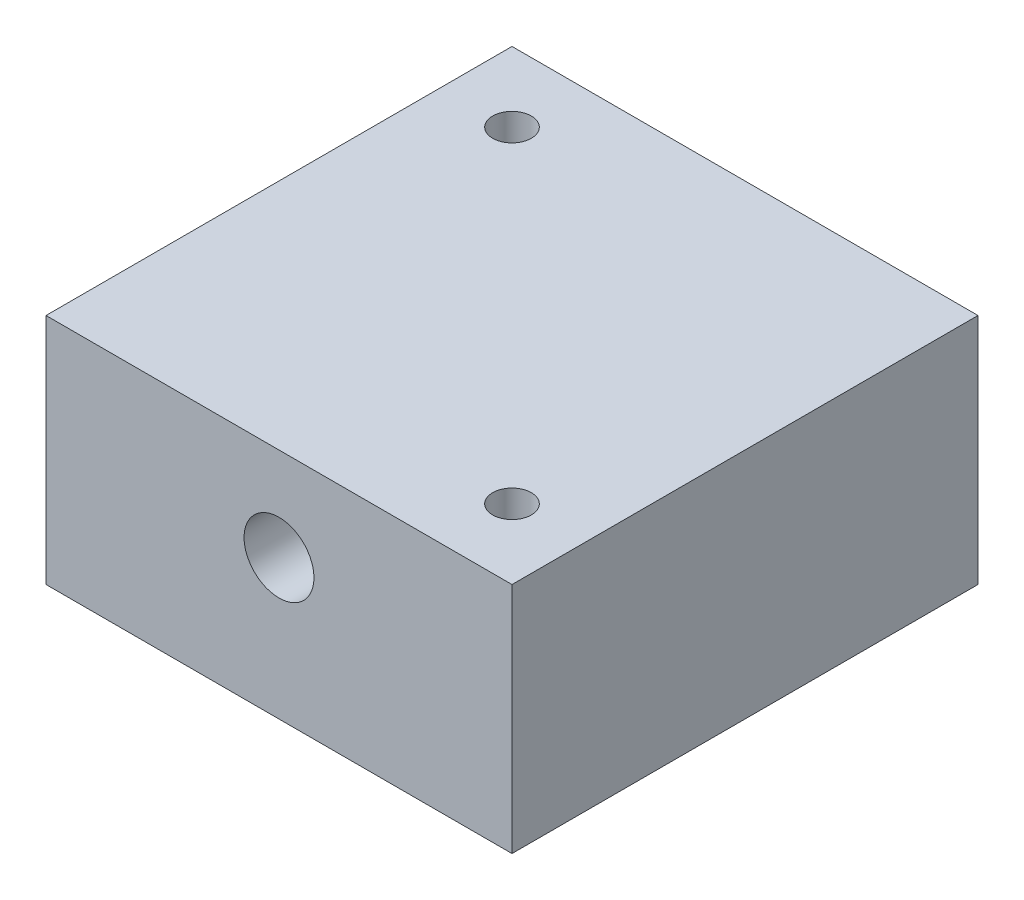
SolidWorks part; units mm, degrees
ref_plane "Ebene vorne" through (0, 0, 0) normal (0, 0, 1) x (1, 0, 0)
ref_plane "Ebene oben" through (0, 0, 0) normal (0, 1, 0) x (1, 0, 0)
ref_plane "Ebene rechts" through (0, 0, 0) normal (1, 0, 0) x (0, 0, -1)
sketch "Skizze1" plane through (0, 0, 0) normal (0, 0, 1) x (1, 0, 0)
  line L1 (50, -25) -> (-50, -25)
  line L2 (50, -25) -> (50, 25)
  line L3 (50, 25) -> (-50, 25)
  line L4 (-50, -25) -> (-50, 25)
  line L5 (50, -25) -> (-50, 25) construction
  line L6 (50, 25) -> (-50, -25) construction
  point P1 (0, 0)
  dimension "D1" = 50
  dimension "D2" = 100
extrude "Aufsatz-Linear austragen1" add sketch "Skizze1" along normal blind 100
sketch "Skizze2" plane through (0, 25, 0) normal (0, 1, 0) x (1, 0, 0)
  line L0 (50, -100) -> (-50, -100) construction
  line L1 (50, -100) -> (50, 0) construction
  line L2 (-50, -100) -> (-50, 0) construction
  line L3 (50, 0) -> (-50, 0) construction
  circle A0 centre (-35, -15) radius 15
  circle A1 centre (35, -85) radius 15
  dimension "D1" = 30
  dimension "D2" = 30
hole_wizard "Kernloch für M8 Helicoil1" positions "Skizze4" profile "Skizze5" hole size "M8x1.25" standard "ANSI Metrisch"
sketch "Skizze4" plane through (0, 25, 0) normal (0, 1, 0) x (1, 0, 0)
  point P0 (35, -85)
  point P5 (-35, -15)
sketch "Skizze5" plane through (35, 25, 85) normal (1, 0, 0) x (0, 0, 1)
  line L0 (0, 0) -> (0, 22.4936)
  line L1 (0, 22.4936) -> (4.15, 20)
  line L2 (4.15, 20) -> (4.15, 0)
  line L5 (4.15, 0) -> (0, 0)
  line L10 (0, 22.4936) -> (-4.15, 20) construction
  line L11 (0, -6.35) -> (0, 107.95) construction
  dimension "Bohrerdurchmesser" = 8.3
  dimension "Bohrungstiefe" = 20
  dimension "Spitzenwinkel" = 118
hole_wizard "Stirnsenkung für M8 Senkschraube (Kopf Button)1" positions "Skizze9" profile "Skizze8" counterbore size "M8" standard "ANSI Metrisch" end condition through all
sketch "Skizze9" plane through (0, 0, 100) normal (0, 0, 1) x (1, 0, 0)
  point P0 (0, 5)
sketch "Skizze8" plane through (0, 5, 100) normal (1, 0, 0) x (0, -1, 0)
  line L0 (0, 0) -> (0, 100)
  line L1 (0, 100) -> (4.5, 100)
  line L3 (4.5, 100) -> (4.5, 116)
  line L4 (4.5, 116) -> (7.5, 116)
  line L5 (7.5, 116) -> (7.5, 0)
  line L7 (7.5, 0) -> (0, 0)
  line L11 (0, -6.35) -> (0, 107.95) construction
  dimension "Bohrerdurchmesser" = 9
  dimension "Bohrungstiefe" = 100
  dimension "Senkdurchmesser2" = 15
  dimension "Senktiefe2" = 116
hole_wizard "Kernloch für M8 Helicoil2" positions "Skizze11" profile "Skizze10" hole size "M8x1.25" standard "ANSI Metrisch"
sketch "Skizze11" plane through (0, 0, 0) normal (0, 0, -1) x (-1, 0, 0)
  point P0 (19.2308, 5.7692)
sketch "Skizze10" plane through (-19.2308, 5.7692, 0) normal (1, 0, 0) x (0, 1, 0)
  line L0 (0, 0) -> (0, 22.4936)
  line L1 (0, 22.4936) -> (4.15, 20)
  line L2 (4.15, 20) -> (4.15, 0)
  line L5 (4.15, 0) -> (0, 0)
  line L10 (0, 22.4936) -> (-4.15, 20) construction
  line L11 (0, -6.35) -> (0, 107.95) construction
  dimension "Bohrerdurchmesser" = 8.3
  dimension "Bohrungstiefe" = 20
  dimension "Spitzenwinkel" = 118
